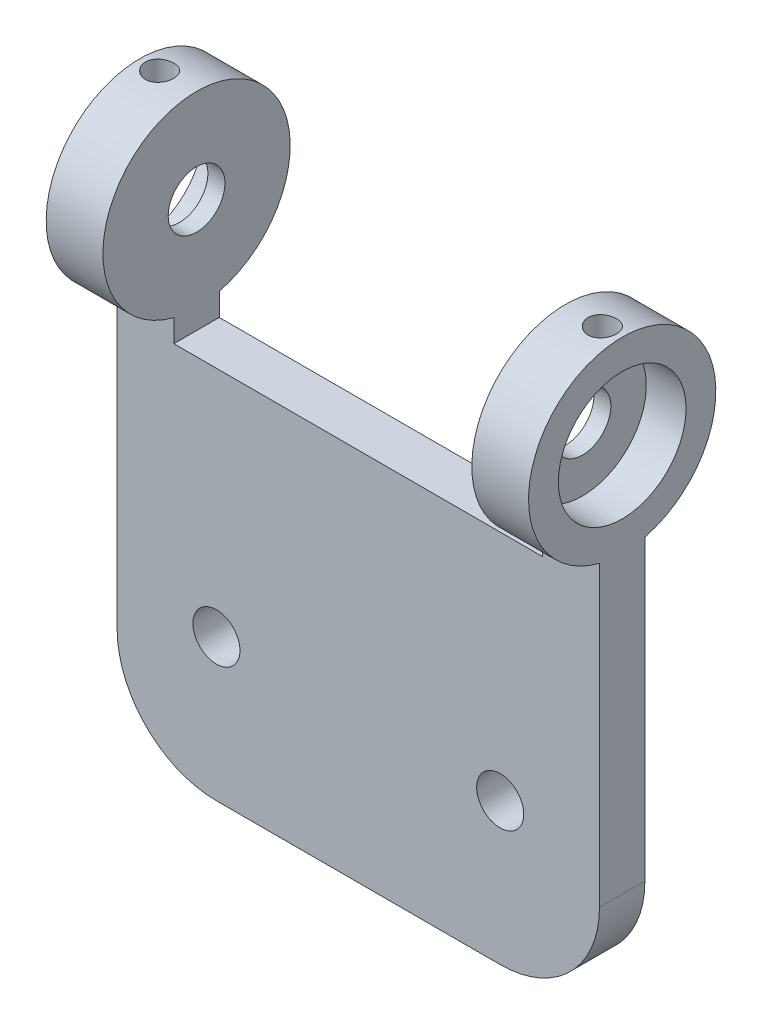
SolidWorks part; units mm, degrees
ref_plane "Front Plane" through (0, 0, 0) normal (0, 0, 1) x (1, 0, 0)
ref_plane "Top Plane" through (0, 0, 0) normal (0, 1, 0) x (1, 0, 0)
ref_plane "Right Plane" through (0, 0, 0) normal (1, 0, 0) x (0, 0, -1)
sketch "Sketch2" plane through (0, 0, 0) normal (0, 0, 1) x (1, 0, 0)
  line L0 (-42.5, 13.75) -> (-32.5, 13.75)
  line L1 (-32.5, 13.75) -> (-32.5, -13.75)
  line L2 (-32.5, -13.75) -> (32.5, -13.75)
  line L3 (32.5, -13.75) -> (32.5, 13.75)
  line L4 (32.5, 13.75) -> (42.5, 13.75)
  line L5 (42.5, 13.75) -> (42.5, -23.75)
  line L6 (42.5, -23.75) -> (-42.5, -23.75)
  line L7 (-42.5, -23.75) -> (-42.5, 13.75)
  line L8 (-32.5, -13.75) -> (32.5, 13.75) construction
  line L9 (-42.5, -23.75) -> (-32.5, -13.75) construction
  line L10 (-32.5, 6.25) -> (32.5, 6.25) construction
  line L11 (0, 6.25) -> (0, -8.75) construction
  point P8 (0, 0)
  dimension "D1" = 10
  dimension "D2" = 10
  dimension "D3" = 65
  dimension "D4" = 15
  dimension "D5" = 5
  dimension "D6" = 7.5
extrude "Boss-Extrude1" add sketch "Sketch2" along normal mid plane 8
sketch "Sketch7" plane through (0, 0, 4) normal (0, 0, 1) x (1, 0, 0)
  line L0 (-25, -54.75) -> (25, -54.75) construction
  line L4 (-25, -29.75) -> (25, -29.75) construction
  line L7 (-42.5, -23.75) -> (-42.5, -62.25)
  line L15 (-25, -79.75) -> (25, -79.75)
  line L16 (42.5, -62.25) -> (42.5, -23.75)
  line L17 (42.5, -23.75) -> (-42.5, -23.75)
  line L18 (0, -29.75) -> (0, -23.75) construction
  arc A16 (-42.5, -62.25) -> (-25, -79.75) centre (-25, -62.25) ccw
  arc A17 (25, -79.75) -> (42.5, -62.25) centre (25, -62.25) ccw
  circle A22 centre (-25, -54.75) radius 25 construction
  circle A23 centre (25, -54.75) radius 25 construction
  circle A24 centre (-25, -54.75) radius 4.15
  circle A25 centre (25, -54.75) radius 4.15
  point P15 (0, -54.75)
  dimension "D1" = 50
  dimension "D2" = 6
  dimension "D3" = 8.3
extrude "Boss-Extrude3" add sketch "Sketch7" against normal up to surface (8 mm away) up to face at (0, -2.5, -4)
ref_plane "Plane1" through (0, 21.25, 0) normal (0, 1, 0) x (1, 0, 0)
sketch "Sketch8" plane through (-42.5, 0, 0) normal (-1, 0, 0) x (0, 0, 1)
  line L0 (0, -23.75) -> (0, 13.75) construction
  circle A0 centre (0, 6.25) radius 11.5 construction
  circle A1 centre (0, 6.25) radius 16.5
  point P4 (0, 6.25)
  dimension "D1" = 23
  dimension "D2" = 5
extrude "Boss-Extrude4" add sketch "Sketch8" against normal blind 10
sketch "Sketch9" plane through (-42.5, 0, 0) normal (-1, 0, 0) x (0, 0, 1)
  circle A0 centre (0, 6.25) radius 11.25
  arc A1 (4, -9.7578) -> (-4, -9.7578) centre (0, 6.25) ccw construction
  dimension "D1" = 22.5
extrude "Cut-Extrude1" cut sketch "Sketch9" against normal blind 7
sketch "Sketch10" plane through (-35.5, 0, 0) normal (-1, 0, 0) x (0, 0, 1)
  circle A0 centre (0, 6.25) radius 5
  circle A1 centre (0, 6.25) radius 11.25 construction
  dimension "D1" = 5
extrude "Cut-Extrude2" cut sketch "Sketch10" against normal blind 3
mirror "Mirror1" about plane through (0, 0, 0) normal (1, 0, 0) of "Cut-Extrude2", "Boss-Extrude4", "Cut-Extrude1"
ref_plane "Plane2" through (0, 22.75, 0) normal (0, 1, 0) x (1, 0, 0)
sketch "Sketch11" plane through (0, 22.75, 0) normal (0, 1, 0) x (1, 0, 0)
  line L0 (-42.5, 16.5) -> (-42.5, -16.5) construction
  line L1 (-35.5, 11.25) -> (-35.5, -11.25) construction
  line L2 (-42.5, 16.5) -> (-42.5, -16.5) construction
  line L3 (-35.5, 11.25) -> (-35.5, -11.25) construction
  line L4 (-42.5, 0) -> (-35.5, 0) construction
  line L5 (39, 0) -> (-39, 0) construction
  circle A0 centre (-39, 0) radius 2.5
  circle A1 centre (39, 0) radius 2.5
  point P12 (0, 0)
  dimension "D1" = 2.5
extrude "Cut-Extrude3" cut sketch "Sketch11" against normal blind 10
